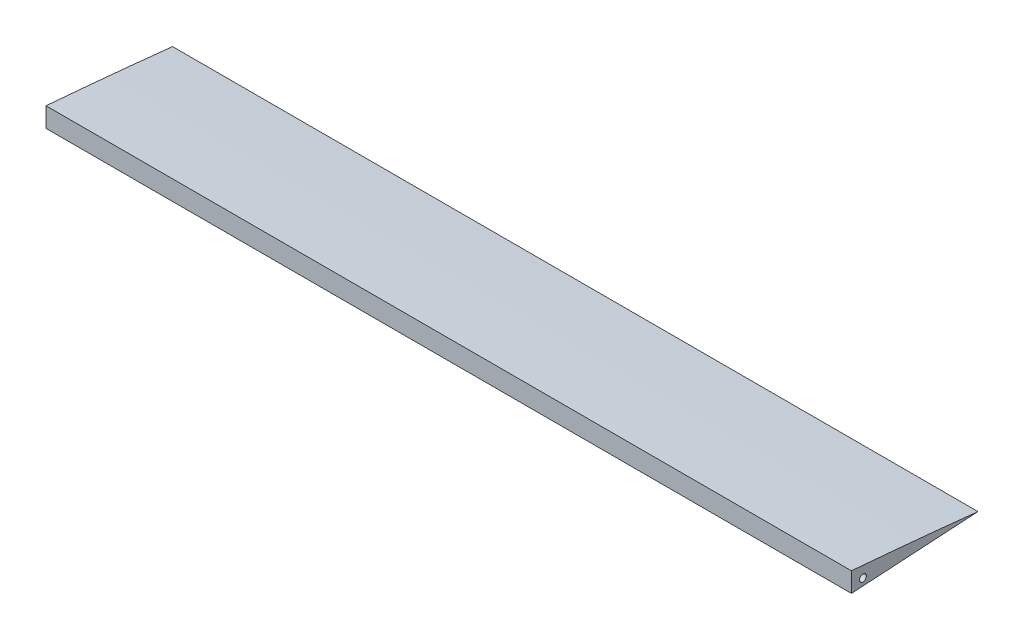
SolidWorks part; units mm, degrees
material "Полиуретановый жесткий пенопласт"
ref_plane "Спереди" through (0, 0, 0) normal (0, 0, 1) x (1, 0, 0)
ref_plane "Сверху" through (0, 0, 0) normal (0, 1, 0) x (1, 0, 0)
ref_plane "Справа" through (0, 0, 0) normal (1, 0, 0) x (0, 0, -1)
sketch "Эскиз1" plane through (0, 0, 0) normal (1, 0, 0) x (0, 0, -1)
  line L0 (-166.0076, 0) -> (272.9886, 0) construction
  line L1 (156.2737, -3.3) -> (211.2737, 0)
  line L2 (156.2737, 5.2262) -> (156.2737, -3.3)
  arc A1 (156.2737, 5.2262) -> (211.2737, 0) centre (-28.8383, -2234.9142) cw
  circle A2 centre (161.2737, 0) radius 1.5
  point P1 (211.2737, 0)
  dimension "D2" = 3
  dimension "D6" = 2247.7756
  dimension "D1" = 55
  dimension "D3" = 50
  dimension "D4" = 8.5262
  dimension "D5" = 3.3
extrude "Бобышка-Вытянуть1" add sketch "Эскиз1" along normal blind 350
